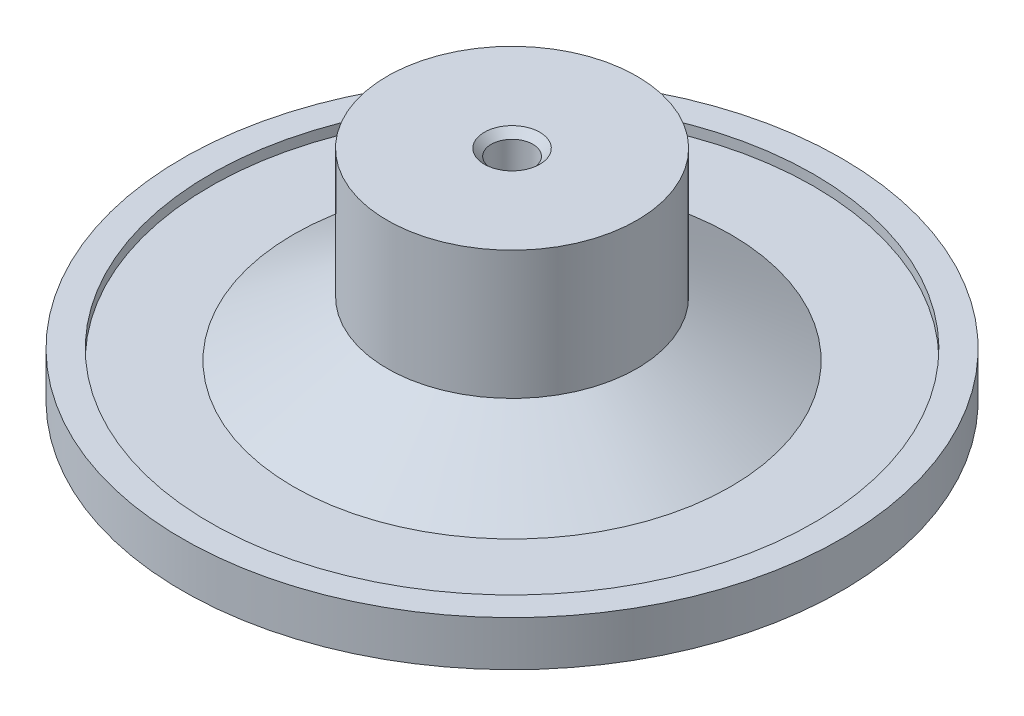
SolidWorks part; units mm, degrees
ref_plane "Front Plane" through (0, 0, 0) normal (0, 0, 1) x (1, 0, 0)
ref_plane "Top Plane" through (0, 0, 0) normal (0, 1, 0) x (1, 0, 0)
ref_plane "Right Plane" through (0, 0, 0) normal (1, 0, 0) x (0, 0, -1)
sketch "Sketch1" plane through (0, 0, 0) normal (0, 0, 1) x (1, 0, 0)
  line L0 (435, -55) -> (475, -55)
  line L1 (475, -55) -> (475, 10)
  line L2 (475, 10) -> (435, 10)
  line L3 (435, 10) -> (435, -5)
  line L4 (435, -5) -> (315, -5)
  line L6 (435, -40) -> (335, -40)
  line L7 (435, -40) -> (435, -55)
  line L9 (225, 0) -> (335, -40)
  line L10 (0, 0) -> (0, 393.7664) construction
  line L11 (30, 250) -> (40, 260)
  line L12 (180, 75) -> (315, -5)
  line L13 (225, 0) -> (30, 0)
  line L14 (180, 75) -> (180, 260)
  line L15 (30, 0) -> (30, 250)
  line L16 (40, 260) -> (180, 260)
  point P11 (30, 260)
  dimension "D1" = 35
  dimension "D2" = 40
  dimension "D3" = 140
  dimension "D4" = 160
  dimension "D5" = 65
  dimension "D6" = 185
  dimension "D7" = 250
  dimension "D8" = 75
  dimension "D9" = 265
  dimension "D10" = 15
  dimension "D11" = 475
  dimension "D12" = 30
  dimension "D13" = 150
revolve "Revolve2" add sketch "Sketch1" angle 360 about L10
